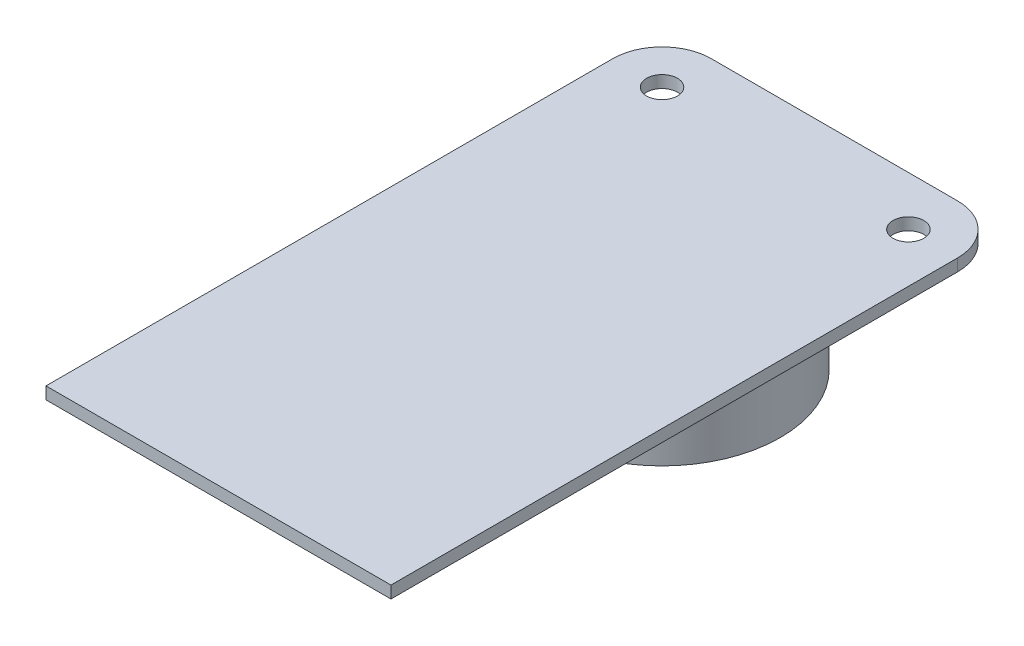
SolidWorks part; units mm, degrees
ref_plane "Front" through (0, 0, 0) normal (0, 0, 1) x (1, 0, 0)
ref_plane "Top" through (0, 0, 0) normal (0, 1, 0) x (1, 0, 0)
ref_plane "Right" through (0, 0, 0) normal (1, 0, 0) x (0, 0, -1)
sketch "Sketch1" plane through (0, 0, 0) normal (0, 1, 0) x (1, 0, 0)
  line L0 (-5.08, 5.08) -> (5.08, 5.08) construction
  line L1 (-5.08, 7.112) -> (5.08, 7.112)
  line L2 (-7.112, 5.08) -> (-7.112, -18.288)
  line L3 (-7.112, -18.288) -> (7.112, -18.288)
  line L4 (7.112, 5.08) -> (7.112, -18.288)
  circle A0 centre (0, 0) radius 4.875 construction
  arc A1 (7.112, 5.08) -> (5.08, 7.112) centre (5.08, 5.08) ccw construction
  arc A2 (-5.08, 7.112) -> (-7.112, 5.08) centre (-5.08, 5.08) ccw construction
  circle A3 centre (5.08, 5.08) radius 0.635
  circle A4 centre (-5.08, 5.08) radius 0.635
  arc A5 (-5.08, 7.112) -> (-7.112, 5.08) centre (-5.08, 5.08) ccw
  arc A6 (7.112, 5.08) -> (5.08, 7.112) centre (5.08, 5.08) ccw
  point P4 (0, 7.112)
  point P12 (0, 5.08)
  dimension "D2" = 9.75
  dimension "D5" = 14.224
  dimension "D6" = 1.27
  dimension "D1" = 25.4
  dimension "D3" = 7.112
  dimension "D4" = 10.16
extrude "Boss-Extrude1" add sketch "Sketch1" along normal blind 0.5
sketch "Sketch2" plane through (0, 0, 0) normal (0, 1, 0) x (1, 0, 0)
  circle A0 centre (0, 0) radius 4.875 construction
  circle A1 centre (0, 0) radius 4.875
extrude "Boss-Extrude2" add sketch "Sketch2" against normal blind 4.5
